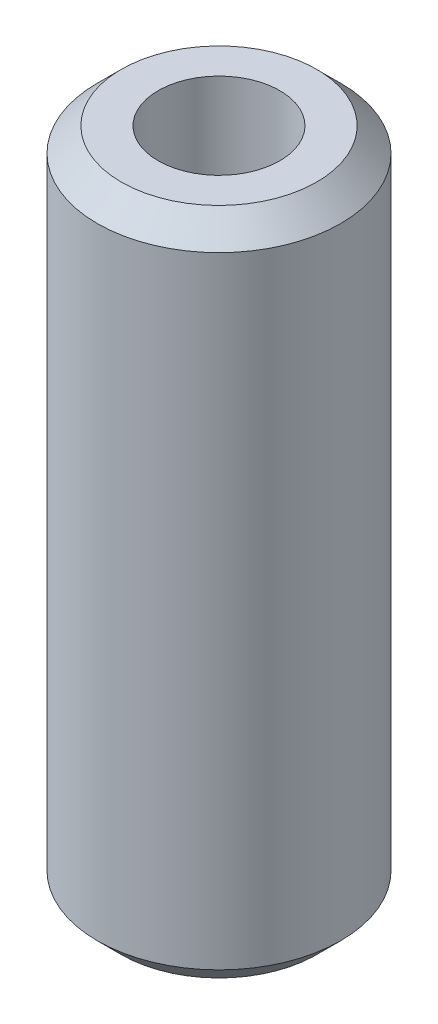
SolidWorks part; units mm, degrees
ref_plane "Front Plane" through (0, 0, 0) normal (0, 0, 1) x (1, 0, 0)
ref_plane "Top Plane" through (0, 0, 0) normal (0, 1, 0) x (1, 0, 0)
ref_plane "Right Plane" through (0, 0, 0) normal (1, 0, 0) x (0, 0, -1)
sketch "Sketch2" plane through (0, 0, 0) normal (0, 1, 0) x (1, 0, 0)
  circle A0 centre (0, 0) radius 12.7
  circle A1 centre (0, 0) radius 6.35
  dimension "D1" = 12.7
  dimension "D2" = 25.4
extrude "Boss-Extrude1" add sketch "Sketch2" along normal mid plane 69.85
chamfer "Chamfer1" distance 2.5 angle 45 2 edges at (0, -34.925, 12.7) (0, 34.925, 12.7)
